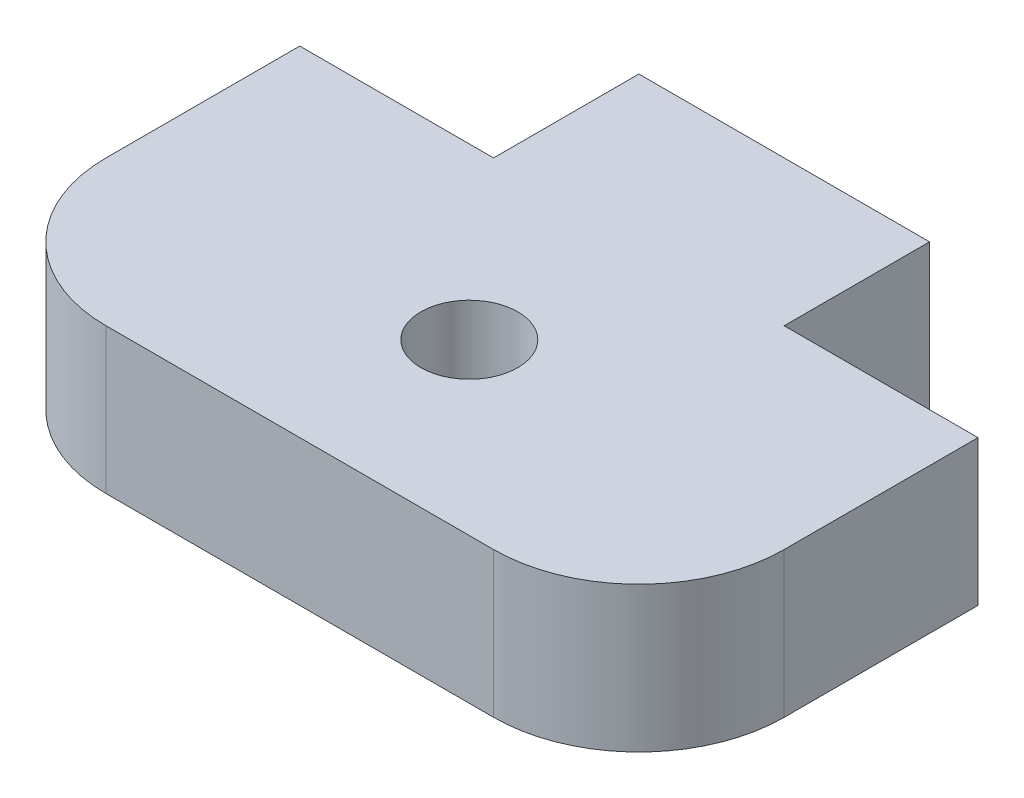
SolidWorks part; units mm, degrees
ref_plane "Plan de face" through (0, 0, 0) normal (0, 0, 1) x (1, 0, 0)
ref_plane "Plan de dessus" through (0, 0, 0) normal (0, 1, 0) x (1, 0, 0)
ref_plane "Plan de droite" through (0, 0, 0) normal (1, 0, 0) x (0, 0, -1)
sketch "Esquisse1" plane through (0, 0, 0) normal (0, 1, 0) x (1, 0, 0)
  line L0 (-7, 7) -> (-3, 7)
  line L1 (3, 10) -> (-3, 10)
  line L2 (7, 7) -> (7, 3)
  line L3 (4, 0) -> (-4, 0)
  line L4 (-7, 7) -> (-7, 3)
  line L5 (0, 0) -> (0, 10) construction
  line L7 (-3, 7) -> (-3, 10)
  line L8 (3, 10) -> (3, 7)
  line L9 (3, 7) -> (7, 7)
  circle A0 centre (0, 3.5) radius 1
  arc A1 (7, 3) -> (4, 0) centre (4, 3) cw
  arc A2 (-4, 0) -> (-7, 3) centre (-4, 3) cw
  point P0 (0, 0)
  point P11 (0, 10)
  point P15 (7, 0)
  point P20 (-7, 0)
  dimension "D5" = 3.5
  dimension "D6" = 2
  dimension "D7" = 3
  dimension "D1" = 10
  dimension "D2" = 14
  dimension "D3" = 6
  dimension "D4" = 3
extrude "Boss.-Extru.1" add sketch "Esquisse1" along normal blind 3
